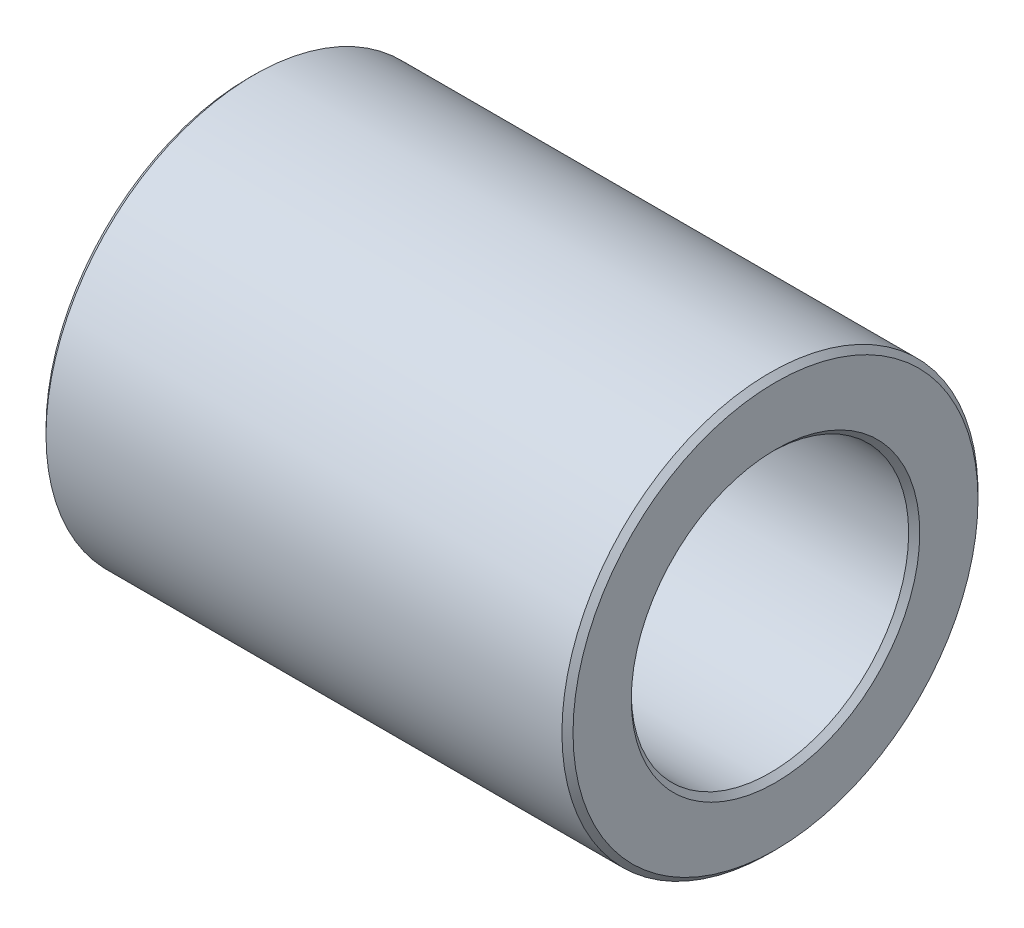
SolidWorks part; units mm, degrees
material "Сталь 45 ГОСТ 1050-88"
ref_plane "Front Plane" through (0, 0, 0) normal (0, 0, 1) x (1, 0, 0)
ref_plane "Top Plane" through (0, 0, 0) normal (0, 1, 0) x (1, 0, 0)
ref_plane "Right Plane" through (0, 0, 0) normal (1, 0, 0) x (0, 0, -1)
sketch "Skizze2" plane through (0, 0, 0) normal (0, 1, 0) x (1, 0, 0)
  line L0 (0, 0) -> (0, 5)
  line L1 (0, 0) -> (0, -5)
  line L2 (0, -5) -> (19, -5)
  line L3 (19, -5) -> (19, 5)
  line L4 (19, 5) -> (0, 5)
  line L5 (0, 0) -> (0, 7.5)
  line L6 (0, 7.5) -> (19, 7.5)
  line L7 (19, 7.5) -> (19, 0)
  line L8 (19, 0) -> (19, -7.5)
  line L9 (19, -7.5) -> (0, -7.5)
  line L10 (0, -7.5) -> (0, 0)
  line L11 (0, 0) -> (19, 0)
revolve "Rotation1" add sketch "Skizze2" angle 360 about L11
chamfer "Fase1" distance 0.2 angle 45 4 edges at (19, 0, 7.5) (19, 0, 5) (0, 0, 7.5) (0, 0, 5)
